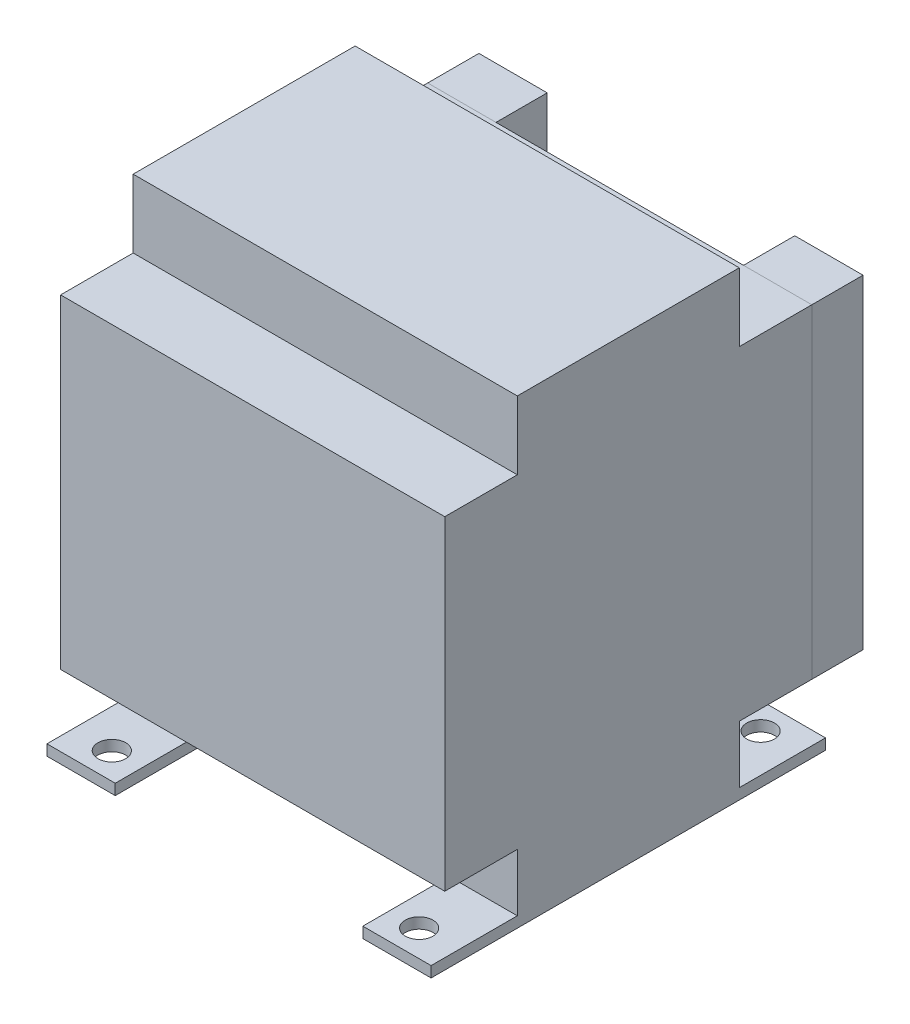
SolidWorks part; units mm, degrees
ref_plane "Front Plane" through (0, 0, 0) normal (0, 0, 1) x (1, 0, 0)
ref_plane "Top Plane" through (0, 0, 0) normal (0, 1, 0) x (1, 0, 0)
ref_plane "Right Plane" through (0, 0, 0) normal (1, 0, 0) x (0, 0, -1)
sketch "Sketch2" plane through (0, 0, 0) normal (0, 0, 1) x (1, 0, 0)
  line L1 (0, 0) -> (71.4375, 0)
  line L2 (0, 0) -> (0, 85.725)
  line L3 (0, 85.725) -> (71.4375, 85.725)
  line L4 (71.4375, 0) -> (71.4375, 85.725)
  dimension "D1" = 71.4375
  dimension "D2" = 85.725
extrude "Boss-Extrude1" add sketch "Sketch2" along normal mid plane 41.275
sketch "Sketch3" plane through (0, 0, 0) normal (0, 0, 1) x (1, 0, 0)
  line L0 (0, 85.725) -> (0, 0) construction
  line L1 (0, 73.025) -> (71.4375, 73.025)
  line L2 (0, 73.025) -> (0, 12.7)
  line L3 (0, 12.7) -> (71.4375, 12.7)
  line L4 (71.4375, 73.025) -> (71.4375, 12.7)
  line L5 (71.4375, 0) -> (71.4375, 85.725) construction
  line L6 (71.4375, 85.725) -> (0, 85.725) construction
  line L7 (0, 0) -> (71.4375, 0) construction
  dimension "D1" = 12.7
  dimension "D2" = 12.7
extrude "Boss-Extrude2" add sketch "Sketch3" along normal mid plane 68.2625
sketch "Sketch4" plane through (0, 0, 0) normal (0, -1, 0) x (1, 0, 0)
  line L0 (0, 34.1313) -> (71.4375, 34.1313) construction
  line L1 (0, 20.6375) -> (12.7, 20.6375)
  line L2 (0, 20.6375) -> (0, 36.6713)
  line L3 (0, 36.6713) -> (12.7, 36.6713)
  line L4 (12.7, 20.6375) -> (12.7, 36.6713)
  line L5 (35.7188, 20.6375) -> (35.7188, -20.6375) construction
  line L6 (0, 20.6375) -> (71.4375, 20.6375) construction
  line L7 (0, -20.6375) -> (71.4375, -20.6375) construction
  line L8 (35.7188, 0) -> (71.4375, 0) construction
  line L9 (71.4375, 20.6375) -> (71.4375, -20.6375) construction
  line L10 (58.7375, 20.6375) -> (58.7375, 36.6713)
  line L11 (71.4375, 36.6713) -> (58.7375, 36.6713)
  line L12 (71.4375, 20.6375) -> (71.4375, 36.6713)
  line L13 (71.4375, 20.6375) -> (58.7375, 20.6375)
  line L14 (71.4375, -20.6375) -> (58.7375, -20.6375)
  line L15 (71.4375, -20.6375) -> (71.4375, -36.6713)
  line L16 (71.4375, -36.6713) -> (58.7375, -36.6713)
  line L17 (58.7375, -20.6375) -> (58.7375, -36.6713)
  line L18 (12.7, -20.6375) -> (12.7, -36.6713)
  line L19 (0, -36.6713) -> (12.7, -36.6713)
  line L20 (0, -20.6375) -> (0, -36.6713)
  line L21 (0, -20.6375) -> (12.7, -20.6375)
  dimension "D1" = 2.54
  dimension "D2" = 12.7
extrude "Boss-Extrude3" add sketch "Sketch4" against normal blind 2
sketch "Sketch5" plane through (0, 0, -34.1313) normal (0, 0, -1) x (-1, 0, 0)
  line L0 (0, 12.7) -> (-71.4375, 12.7) construction
  line L1 (-71.4375, 73.025) -> (-58.7375, 73.025)
  line L2 (-71.4375, 73.025) -> (-71.4375, 12.7)
  line L3 (-71.4375, 12.7) -> (-58.7375, 12.7)
  line L4 (-58.7375, 73.025) -> (-58.7375, 12.7)
  line L5 (-71.4375, 73.025) -> (0, 73.025) construction
  line L6 (0, 12.7) -> (-12.7, 12.7)
  line L7 (0, 12.7) -> (0, 73.025)
  line L8 (0, 73.025) -> (-12.7, 73.025)
  line L9 (-12.7, 12.7) -> (-12.7, 73.025)
  dimension "D1" = 12.7
extrude "Boss-Extrude4" add sketch "Sketch5" along normal blind 9.525 separate body
sketch "Sketch6" plane through (0, 0, 0) normal (0, -1, 0) x (1, 0, 0)
  line L0 (35.7187, 20.6375) -> (35.7188, 0) construction
  line L1 (64.2937, -31.75) -> (7.1437, -31.75) construction
  line L2 (64.2937, -31.75) -> (64.2937, 31.75) construction
  line L3 (64.2937, 31.75) -> (7.1437, 31.75) construction
  line L4 (7.1437, -31.75) -> (7.1437, 31.75) construction
  line L5 (64.2937, -31.75) -> (7.1437, 31.75) construction
  line L6 (64.2937, 31.75) -> (7.1437, -31.75) construction
  line L7 (12.7, 20.6375) -> (58.7375, 20.6375) construction
  circle A0 centre (7.1437, 31.75) radius 2.5797
  circle A1 centre (64.2937, 31.75) radius 2.5797
  circle A2 centre (64.2937, -31.75) radius 2.5797
  circle A3 centre (7.1437, -31.75) radius 2.5797
  point P0 (35.7187, 0)
  dimension "D1" = 5.1594
  dimension "D2" = 57.15
  dimension "D3" = 63.5
extrude "Cut-Extrude1" cut sketch "Sketch6" against normal up to surface (2 mm away) up to face at (6.35, 2, 28.6544)
sketch "Sketch7" plane through (0, 0, 0) normal (0, -1, 0) x (1, 0, 0)
  line L0 (0, 0) -> (71.4375, 0) construction
  line L1 (71.4375, 36.6713) -> (71.4375, -36.6713) construction
  line L2 (35.7188, -38.1) -> (35.7187, 38.1) construction
  line L3 (48.4187, 44.45) -> (23.0188, 44.45)
  line L4 (23.0188, 31.75) -> (48.4187, 31.75)
  line L5 (23.0188, -31.75) -> (48.4187, -31.75)
  line L6 (48.4187, -44.45) -> (23.0188, -44.45)
  circle A0 centre (35.7187, 38.1) radius 6.35 construction
  arc A1 (23.0188, 44.45) -> (23.0188, 31.75) centre (23.0188, 38.1) ccw
  arc A2 (48.4187, 44.45) -> (48.4187, 31.75) centre (48.4187, 38.1) cw
  arc A3 (48.4187, -44.45) -> (48.4187, -31.75) centre (48.4187, -38.1) ccw
  arc A4 (23.0188, -44.45) -> (23.0188, -31.75) centre (23.0188, -38.1) cw
  point P7 (35.7188, 0)
  point P8 (35.7188, 0)
  point P20 (35.7188, 31.75)
  point P22 (35.7188, 44.45)
  dimension "D1" = 12.7
  dimension "D2" = 76.2
  dimension "D3" = 12.7
extrude "Boss-Extrude5" add sketch "Sketch7" along normal blind 2 separate body contours A4 L6 A3 L5
